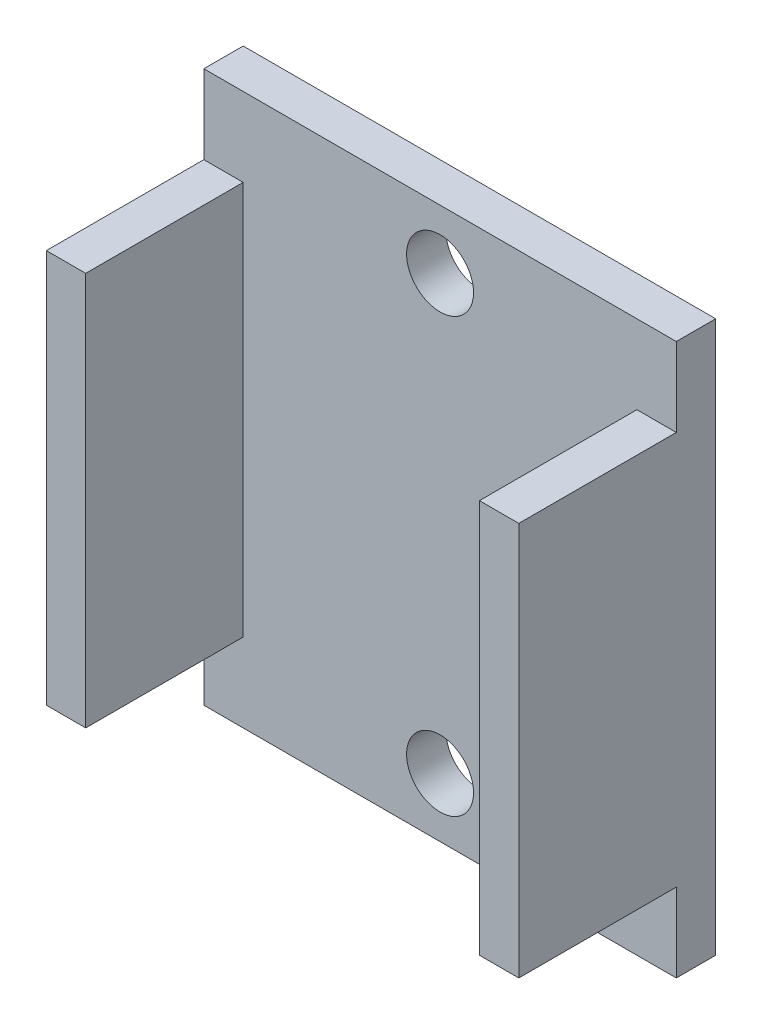
SolidWorks part; units mm, degrees
other "Fuse Holder Clip"
ref_plane "Front Plane" through (0, 0, 0) normal (0, 0, 1) x (1, 0, 0)
ref_plane "Top Plane" through (0, 0, 0) normal (0, 1, 0) x (1, 0, 0)
ref_plane "Right Plane" through (0, 0, 0) normal (1, 0, 0) x (0, 0, -1)
sketch3d "Main Profile Sketch datum points"
  point P0 (0, 0, 88)
  point P1 (10, 0, 88)
  point P2 (0, 10, 88)
ref_plane "Main Profile Sketch plane" through (0, 0, 88) normal (0, 0, 1) x (1, 0, 0)
sketch "Main Profile Sketch" plane through (0, 0, 88) normal (0, 0, 1) x (1, 0, 0)
  line L0 (-178, 14) -> (-178, -14)
  line L1 (-202, -14) -> (-178, -14)
  line L2 (-202, 14) -> (-202, -14)
  line L3 (-202, 14) -> (-178, 14)
  circle A0 centre (-190, -11) radius 1.7
  circle A1 centre (-190, 11) radius 1.7
extrude "Main Extrusion" add sketch "Main Profile Sketch" along normal blind 2 separate body
sketch3d "Detail Profile 2 Sketch datum points"
  point P0 (0, 0, 90)
  point P1 (10, 0, 90)
  point P2 (0, 10, 90)
ref_plane "Detail Profile 2 Sketch plane" through (0, 0, 90) normal (0, 0, 1) x (1, 0, 0)
sketch "Detail Profile 2 Sketch" plane through (0, 0, 90) normal (0, 0, 1) x (1, 0, 0)
  line L0 (-180, 10) -> (-178, 10)
  line L1 (-178, 10) -> (-178, -10)
  line L2 (-180, -10) -> (-178, -10)
  line L3 (-180, 10) -> (-180, -10)
  line L4 (-202, 10) -> (-200, 10)
  line L5 (-200, 10) -> (-200, -10)
  line L6 (-202, -10) -> (-200, -10)
  line L7 (-202, 10) -> (-202, -10)
extrude "Detail Extrusion 2" add sketch "Detail Profile 2 Sketch" along normal blind 8
